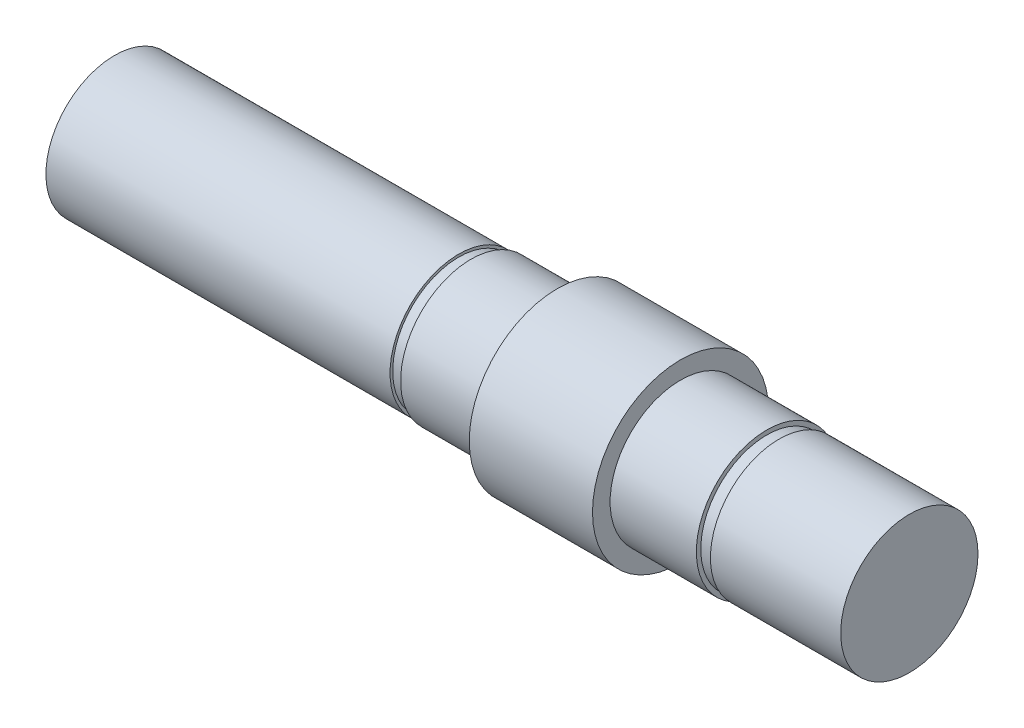
SolidWorks part; units mm, degrees
material "5052-H32"
ref_plane "Front Plane" through (0, 0, 0) normal (0, 0, 1) x (1, 0, 0)
ref_plane "Top Plane" through (0, 0, 0) normal (0, 1, 0) x (1, 0, 0)
ref_plane "Right Plane" through (0, 0, 0) normal (1, 0, 0) x (0, 0, -1)
sketch "Sketch1" plane through (0, 0, 0) normal (0, 0, 1) x (1, 0, 0)
  line L0 (0, 0) -> (-45.15, 0)
  line L1 (-45.15, 0) -> (-45.15, 3.9)
  line L2 (-45.15, 3.9) -> (-25.6, 3.9)
  line L3 (-25.6, 3.9) -> (-25.6, 3.75)
  line L4 (-25.6, 3.75) -> (-24.9, 3.75)
  line L5 (-24.9, 3.75) -> (-24.9, 4)
  line L6 (-24.9, 4) -> (-20, 4)
  line L7 (-20, 4) -> (-20, 5)
  line L8 (-20, 5) -> (-13, 5)
  line L9 (-13, 5) -> (-13, 4)
  line L10 (-13, 4) -> (-8.1, 4)
  line L11 (-8.1, 4) -> (-8.1, 3.75)
  line L12 (-8.1, 3.75) -> (-7.4, 3.75)
  line L13 (-7.4, 3.75) -> (-7.4, 3.9)
  line L14 (-7.4, 3.9) -> (0, 3.9)
  line L15 (0, 3.9) -> (0, 0)
  line L18 (-8, 121.2) -> (-8, 3.75) construction
  line L19 (-8, 121.2) -> (-8, 4.6026) construction
  line L20 (-25, 121.2) -> (-25, 3.75) construction
  line L21 (-25, 3.418) -> (-25, 121.2) construction
revolve "Revolve1" add sketch "Sketch1" angle 360 about L0
sketch "Sketch2" plane through (0, 0, 0) normal (1, 0, 0) x (0, 0, -1)
  line L0 (2, -3.3481) -> (-2, -3.3481)
  arc A0 (-2, -3.3481) -> (2, -3.3481) centre (0, 0) ccw
  circle A1 centre (0, 0) radius 3.9 construction
extrude "Cut-Extrude2" cut sketch "Sketch2" against normal up to vertex from vertex
sketch "Sketch3" [suppressed] plane through (0, 0, 0) normal (0, 0, 1) x (1, 0, 0)
  line L0 (0, 2) -> (8, 2)
  line L1 (8, 2) -> (8, 0)
  line L2 (8, 0) -> (0, 0)
  line L3 (0, 2) -> (0, 0)
revolve "Revolve2" [suppressed] add sketch "Sketch3" angle 360 about L2
